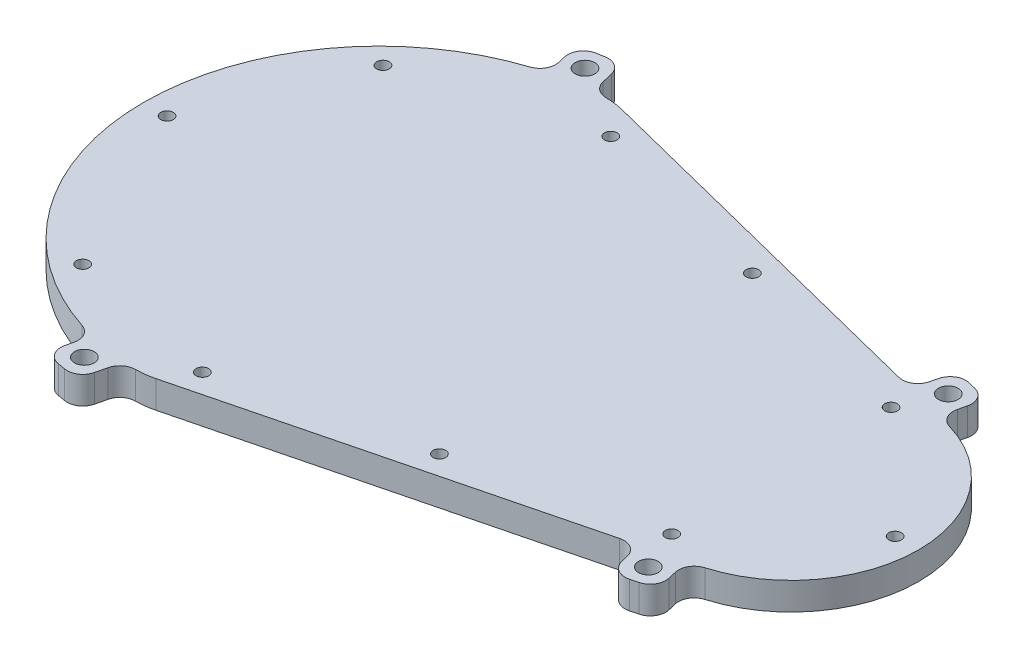
SolidWorks part; units mm, degrees
ref_plane "Ön Düzlem" through (0, 0, 0) normal (0, 0, 1) x (1, 0, 0)
ref_plane "Üst Düzlem" through (0, 0, 0) normal (0, 1, 0) x (1, 0, 0)
ref_plane "Sağ Düzlem" through (0, 0, 0) normal (1, 0, 0) x (0, 0, -1)
sketch "Sketch1" plane through (0, 0, 0) normal (0, 1, 0) x (1, 0, 0)
  line L0 (71.164, -24.7436) -> (-40.8113, -52.9862) construction
  line L1 (-40.8113, 55.004) -> (71.164, 26.7614) construction
  line L2 (-40.0856, -58.9911) -> (72.6066, -30.5677)
  line L3 (72.6066, 32.5855) -> (-40.0856, 61.0089)
  line L4 (0, 0) -> (97.4144, 1.0089) construction
  arc A0 (-40.8113, -52.9862) -> (-40.8113, 55.004) centre (-40.0856, 1.0089) cw construction
  arc A1 (71.164, -24.7436) -> (71.164, 26.7614) centre (64.9144, 1.0089) ccw construction
  circle A2 centre (15.1764, -38.8649) radius 1.6
  circle A3 centre (-33.0542, -51.0297) radius 1.6
  circle A4 centre (62.4373, -26.9447) radius 1.6
  circle A5 centre (91.4144, 1.0089) radius 1.6
  circle A6 centre (-33.0542, 53.0475) radius 1.6
  circle A7 centre (15.1764, 40.8827) radius 1.6
  circle A8 centre (62.4373, 28.9625) radius 1.6
  circle A9 centre (-94.0856, 1.0089) radius 1.6
  circle A10 centre (-72.1252, -42.4591) radius 1.6
  circle A11 centre (-77.7642, 39.6912) radius 1.6
  arc A12 (72.6066, -30.5677) -> (72.6066, 32.5855) centre (64.9144, 1.0089) ccw
  arc A13 (-40.0856, -58.9911) -> (-40.0856, 61.0089) centre (-40.0856, 1.0089) cw
  dimension "D3" = 26.5
  dimension "D4" = 54
  dimension "D10" = 3.2
  dimension "D11" = 32.5
  dimension "D14" = 97.4144
  dimension "D1" = 8
  dimension "D2" = 8
  dimension "D5" = 51.505
  dimension "D6" = 9
  dimension "D7" = 9
  dimension "D8" = 40
  dimension "D9" = 40
  dimension "D12" = 116.2214
  dimension "D13" = 120
extrude "Boss-Extrude1" add sketch "Sketch1" along normal blind 7
sketch "Sketch2" plane through (0, 7, 0) normal (0, 1, 0) x (1, 0, 0)
  line L0 (-55.1493, 59.0871) -> (-45.294, 60.7824)
  line L1 (-55.1493, 59.0871) -> (-57.4625, 68.8159)
  line L2 (-45.294, 60.7824) -> (-47.6073, 70.5112)
  line L3 (-57.4625, 68.8159) -> (-47.6073, 70.5112)
  line L4 (60.7377, 35.579) -> (70.4341, 33.1334)
  line L5 (60.7377, 35.579) -> (63.0733, 45.3025)
  line L6 (70.4341, 33.1334) -> (72.7696, 42.8569)
  line L7 (63.0733, 45.3025) -> (72.7696, 42.8569)
  line L8 (72.6066, 32.5855) -> (-40.0856, 61.0089) construction
  line L9 (-100.0856, 1.0089) -> (-45.294, 1.0089) construction
  line L10 (63.0733, -43.2847) -> (72.7696, -40.8391)
  line L11 (70.4341, -31.1157) -> (72.7696, -40.8391)
  line L12 (60.7377, -33.5613) -> (63.0733, -43.2847)
  line L13 (60.7377, -33.5613) -> (70.4341, -31.1157)
  line L14 (-57.4625, -66.7982) -> (-47.6073, -68.4934)
  line L15 (-45.294, -58.7646) -> (-47.6073, -68.4934)
  line L16 (-55.1493, -57.0694) -> (-57.4625, -66.7982)
  line L17 (-55.1493, -57.0694) -> (-45.294, -58.7646)
  arc A0 (-40.0856, 61.0089) -> (-40.0856, -58.9911) centre (-40.0856, 1.0089) ccw construction
  dimension "D1" = 10
  dimension "D2" = 10
  dimension "D3" = 10
  dimension "D4" = 10
extrude "Boss-Extrude2" add sketch "Sketch2" against normal up to vertex (7 mm away)
sketch "Sketch3" plane through (0, 7, 0) normal (0, 1, 0) x (1, 0, 0)
  line L1 (-47.6073, 70.5112) -> (-57.4625, 68.8159) construction
  line L2 (-45.294, 60.7824) -> (-47.6073, 70.5112) construction
  line L3 (70.4341, 33.1334) -> (72.7696, 42.8569) construction
  line L4 (72.7696, 42.8569) -> (63.0733, 45.3025) construction
  line L5 (-77.8664, 1.0089) -> (-100.0856, 1.0089) construction
  circle A0 centre (-51.3858, 64.7878) radius 2.5
  circle A1 centre (66.7533, 39.2177) radius 2.5
  arc A2 (-55.1493, 59.0871) -> (-55.1493, -57.0694) centre (-40.0856, 1.0089) ccw construction
  circle A3 centre (66.7533, -37.2) radius 2.5
  circle A4 centre (-51.3858, -62.77) radius 2.5
  dimension "D1" = 5
  dimension "D6" = 5
  dimension "D2" = 5
  dimension "D3" = 5
  dimension "D4" = 5
  dimension "D5" = 5
extrude "Cut-Extrude1" cut sketch "Sketch3" against normal blind 7
fillet "Fillet1" radius 4 16 edges at (-55.1493, 3.5, 57.0694) (-57.4625, 3.5, 66.7982) (-47.6073, 3.5, 68.4934) (-45.294, 3.5, 58.7646) (70.4341, 3.5, 31.1157) (72.7696, 3.5, 40.8391) (63.0733, 3.5, 43.2847) (60.7377, 3.5, 33.5613) (60.7377, 3.5, -35.579) (63.0733, 3.5, -45.3025) (72.7696, 3.5, -42.8569) (70.4341, 3.5, -33.1334) (-45.294, 3.5, -60.7824) (-55.1493, 3.5, -59.0871) (-47.6073, 3.5, -70.5112) (-57.4625, 3.5, -68.8159)
fillet "Fillet2" radius 20 2 edges at (-40.0856, 3.5, 58.9911) (-40.0856, 3.5, -61.0089)
sketch "Sketch5" plane through (0, 0, 0) normal (0, -1, 0) x (1, 0, 0)
  circle A0 centre (-45.0856, -1.0089) radius 20
  circle A1 centre (64.9144, -1.0089) radius 3
  arc A2 (-58.68, 56.0371) -> (-58.68, -58.0549) centre (-40.0856, -1.0089) ccw construction
  dimension "D1" = 40
  dimension "D2" = 6
  dimension "D3" = 5
  dimension "D4" = 0
extrude "Cut-Extrude3" cut sketch "Sketch5" against normal blind 2
